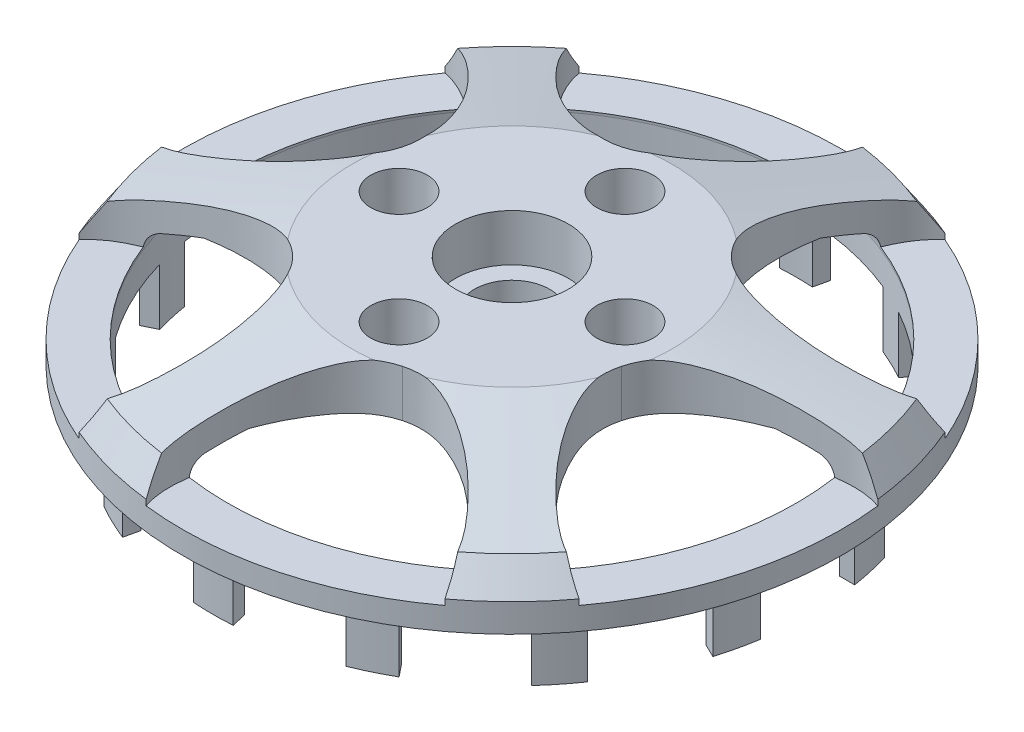
SolidWorks part; units mm, degrees
ref_plane "Спереди" through (0, 0, 0) normal (0, 0, 1) x (1, 0, 0)
ref_plane "Сверху" through (0, 0, 0) normal (0, 1, 0) x (1, 0, 0)
ref_plane "Справа" through (0, 0, 0) normal (1, 0, 0) x (0, 0, -1)
sketch "Эскиз2" plane through (0, 0, 0) normal (0, 0, 1) x (1, 0, 0)
  line L0 (0, 0) -> (0, 28.5055) construction
  line L1 (0, 0) -> (8.5, 0)
  line L2 (8.5, 0) -> (16.5, -2)
  line L3 (16.5, -2) -> (17.5, -3.5)
  line L4 (17.5, -3.5) -> (17.5, -5)
  line L5 (15.1, -8.5) -> (15.9, -8.5)
  line L6 (15.1, -8.5) -> (15.1, -3.15)
  line L7 (15.1, -3.15) -> (12.5, -2.5)
  line L8 (12.5, -2.5) -> (5.5, -2.5)
  line L9 (5.5, -2.5) -> (5.5, -4.5)
  line L10 (5.5, -4.5) -> (3, -5.5)
  line L11 (3, -5.5) -> (0, -5.5)
  line L12 (40.1518, 400.4586) -> (666.8184, 400.4586) construction
  line L15 (17.5, -5) -> (15.9, -5)
  line L16 (15.9, -8.5) -> (15.9, -5)
  line L17 (0, 0) -> (0, -5.5)
  point P8 (5.5, -3.5)
  dimension "D1" = 1.6
  dimension "D2" = 17.5
  dimension "D3" = 15.1
  dimension "D4" = 8.5
  dimension "D5" = 5.5
  dimension "D6" = 12.5
  dimension "D7" = 2.5
  dimension "D8" = 3
  dimension "D9" = 5.5
  dimension "D10" = 8.5
  dimension "D11" = 1.5
  dimension "D12" = 5
  dimension "D13" = 2
  dimension "D14" = 16.5
  dimension "D15" = 6.5
revolve "Повернуть1" add sketch "Эскиз2" angle 360 about L0
sketch "Эскиз3" plane through (0, 0, 0) normal (0, 1, 0) x (1, 0, 0)
  circle A0 centre (0, 0) radius 2
  circle A1 centre (0, 6) radius 1.5
  circle A2 centre (6, 0) radius 1.5
  circle A3 centre (0, -6) radius 1.5
  circle A4 centre (-6, 0) radius 1.5
  point P14 (0, 0)
  dimension "D1" = 4
  dimension "D2" = 3
  dimension "D3" = 6
  dimension "D4" = 4
extrude "Вырез-Вытянуть1" cut sketch "Эскиз3" against normal through all
sketch "Эскиз4" plane through (0, -8.5, 0) normal (0, -1, 0) x (1, 0, 0)
  line L0 (-12.2474, 2.5) -> (-12.2474, -2.5)
  line L1 (-20.0435, -2.5) -> (-12.2474, -2.5)
  line L2 (-20.0435, -2.5) -> (-20.0435, 2.5)
  line L3 (-20.0435, 2.5) -> (-12.2474, 2.5)
  line L4 (20.0435, -2.5) -> (20.0435, 2.5)
  line L5 (-20.0435, -2.5) -> (-12.2474, -1.5276) construction
  line L6 (-20.0435, 2.5) -> (-12.2474, 1.5276) construction
  line L7 (13.0614, 2.5) -> (13.0614, -2.5)
  line L8 (13.0614, 2.5) -> (20.0435, 2.5)
  line L9 (13.0614, -1.6291) -> (20.0435, -2.5) construction
  line L10 (13.0614, 1.6291) -> (20.0435, 2.5) construction
  line L11 (13.0614, -2.5) -> (20.0435, -2.5)
  circle A0 centre (0, 0) radius 12.5 construction
  point P0 (0, 0)
  dimension "D1" = 5
extrude "Вырез-Вытянуть2" cut sketch "Эскиз4" against normal blind 3
pattern_circular "Круговой массив1" count 14 over 360 about axis through (0, 0, 0) along (0, 1, 0) of "Вырез-Вытянуть2"
fillet "Скругление1" radius 1 1 edges at (0, -3.15, -15.1)
sketch "Эскиз5" plane through (0, 0, 0) normal (0, 1, 0) x (1, 0, 0)
  line L0 (-207.9523, 246.5567) -> (235.1679, 689.677) construction
  line L1 (0, 0) -> (14.9982, 14.9982) construction
  line L2 (6.9159, 16.0755) -> (13.0698, 17.3074)
  line L3 (13.0698, 17.3074) -> (17.7343, 13.3888)
  line L4 (17.7343, 13.3888) -> (16.0755, 6.9159)
  circle A0 centre (0, 0) radius 17.5 construction
  spline S0 degree 3 poles (6.9159, 16.0755) (6.0859, 15.3591) (4.9634, 12.8886) (4.3625, 9.1426) (5.0679, 6.5804) (5.8229, 5.8229) knots 0 0 0 0 0.287312 0.736997 1 1 1 1
  spline S1 degree 3 poles (16.0755, 6.9159) (15.3591, 6.0859) (12.8886, 4.9634) (9.1426, 4.3625) (6.5804, 5.0679) (5.8229, 5.8229) knots 0 0 0 0 0.287312 0.736997 1 1 1 1
extrude "Вырез-Вытянуть5" cut sketch "Эскиз5" against normal blind 3.8
pattern_circular "Круговой массив2" count 6 over 360 about axis through (0, -8.5, 0) along (0, 1, 0) of "Вырез-Вытянуть5"
sketch "Эскиз6" plane through (0, 0, 0) normal (0, 1, 0) x (1, 0, 0)
  circle A0 centre (0, 0) radius 3
  dimension "D1" = 6
extrude "Вырез-Вытянуть6" cut sketch "Эскиз6" against normal blind 2.5
